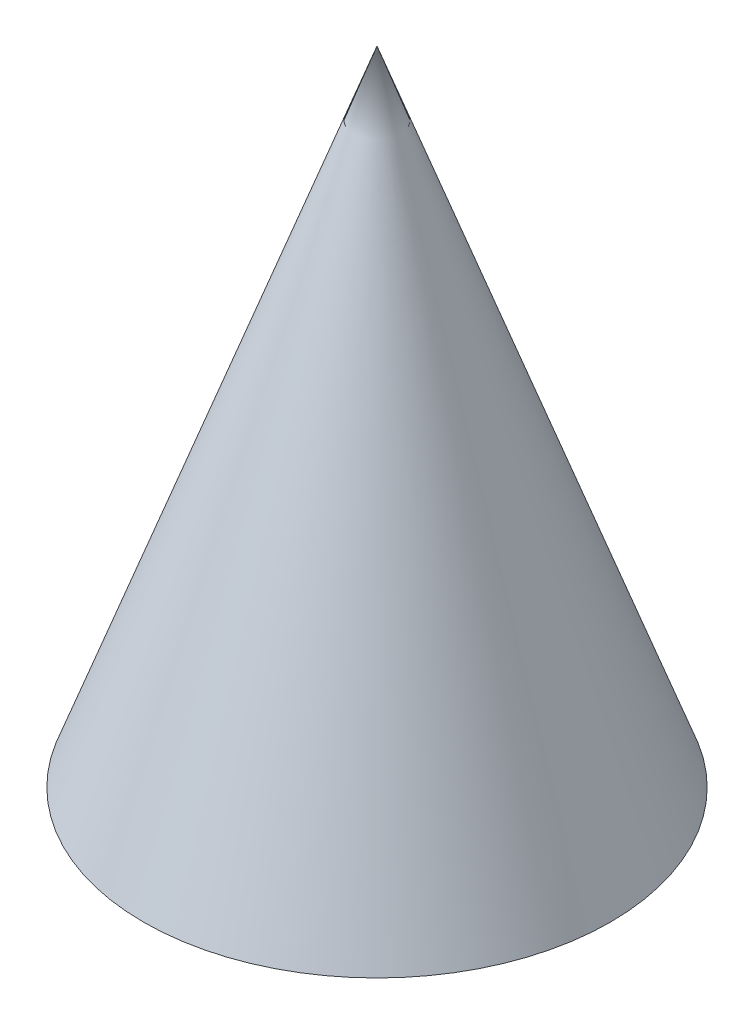
SolidWorks part; units mm, degrees
ref_plane "Front Plane" through (0, 0, 0) normal (0, 0, 1) x (1, 0, 0)
ref_plane "Top Plane" through (0, 0, 0) normal (0, 1, 0) x (1, 0, 0)
ref_plane "Right Plane" through (0, 0, 0) normal (1, 0, 0) x (0, 0, -1)
sketch "Sketch1" plane through (0, 0, 0) normal (0, 0, 1) x (1, 0, 0)
  line L0 (0, 0) -> (0, 55)
  line L1 (0, 55) -> (20, 0)
  line L2 (20, 0) -> (0, 0)
  dimension "D1" = 55
  dimension "D2" = 20
revolve "Revolve1" add sketch "Sketch1" angle 360 about L0
sketch "Sketch2" plane through (0, 0, 0) normal (0, -1, 0) x (1, 0, 0)
  point P0 (0, 0)
